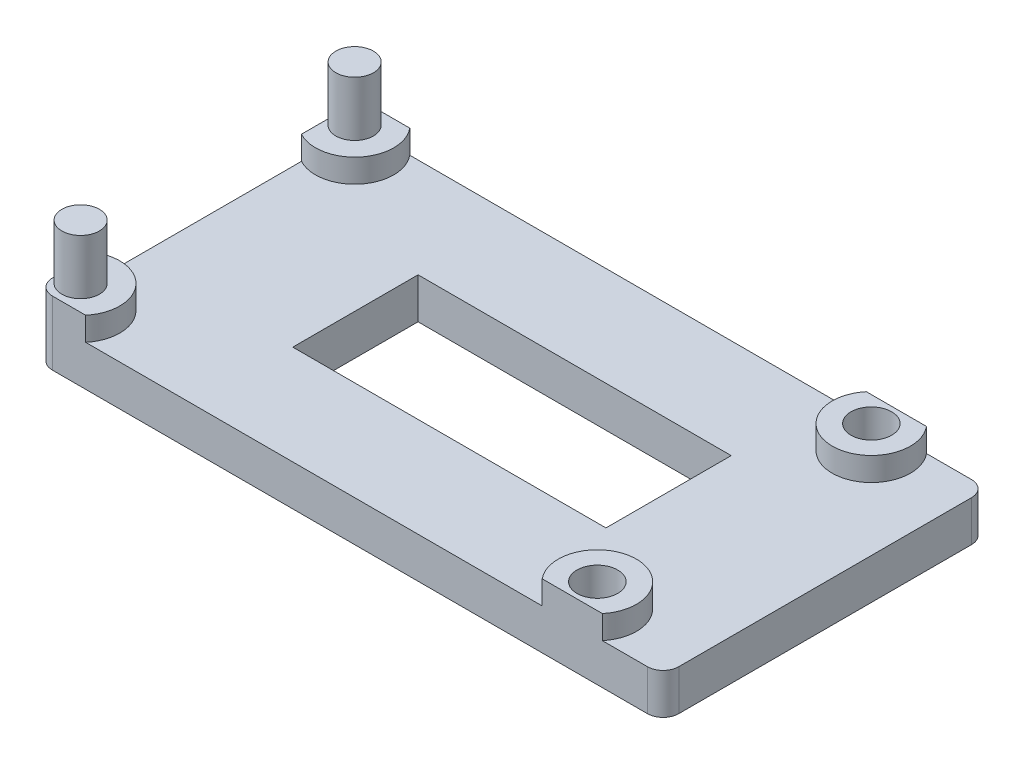
SolidWorks part; units mm, degrees
ref_plane "Front Plane" through (0, 0, 0) normal (0, 0, 1) x (1, 0, 0)
ref_plane "Top Plane" through (0, 0, 0) normal (0, 1, 0) x (1, 0, 0)
ref_plane "Right Plane" through (0, 0, 0) normal (1, 0, 0) x (0, 0, -1)
sketch "Sketch1" plane through (0, 0, 0) normal (0, 1, 0) x (1, 0, 0)
  line L1 (-20, -10.35) -> (20, -10.35)
  line L2 (-20, -10.35) -> (-20, 10.35)
  line L3 (-20, 10.35) -> (20, 10.35)
  line L4 (20, -10.35) -> (20, 10.35)
  line L5 (-20, -10.35) -> (20, 10.35) construction
  line L6 (-20, 10.35) -> (20, -10.35) construction
  point P0 (0, 0)
  dimension "D1" = 20.7
  dimension "D2" = 40
extrude "Boss-Extrude1" add sketch "Sketch1" along normal blind 4.1
sketch "Sketch2" plane through (0, 4.1, 0) normal (0, 1, 0) x (1, 0, 0)
  line L0 (-20, 10.35) -> (-20, -10.35) construction
  line L1 (-18.8, 8.75) -> (-18.8, -8.75) construction
  line L2 (-18.8, 0) -> (-20, 0) construction
  circle A0 centre (-18.8, 8.75) radius 1.2
  circle A1 centre (-18.8, -8.75) radius 1.2
  dimension "D1" = 2.4
  dimension "D2" = 17.5
extrude "Boss-Extrude2" add sketch "Sketch2" along normal blind 3.5
sketch "Sketch3" plane through (0, 4.1, 0) normal (0, 1, 0) x (1, 0, 0)
  line L0 (-18.8, 8.75) -> (20, 8.75) construction
  line L1 (20, -10.35) -> (20, 10.35) construction
  line L2 (-18.8, -8.75) -> (20, -8.75) construction
  line L3 (14.2, 8.75) -> (14.2, -8.75) construction
  circle A0 centre (14.2, 8.75) radius 1.3
  circle A1 centre (14.2, -8.75) radius 1.3
  dimension "D2" = 2.6
  dimension "D1" = 33
extrude "Cut-Extrude1" cut sketch "Sketch3" against normal through all
fillet "Fillet1" radius 1 4 edges at (-20, 2.05, -10.35) (20, 2.05, -10.35) (20, 2.05, 10.35) (-20, 2.05, 10.35)
sketch "Sketch4" plane through (0, 4.1, 0) normal (0, 1, 0) x (1, 0, 0)
  line L1 (-24.095, 13.8953) -> (24.8046, 13.8953)
  line L2 (-24.095, 13.8953) -> (-24.095, -14.4275)
  line L3 (-24.095, -14.4275) -> (24.8046, -14.4275)
  line L4 (24.8046, 13.8953) -> (24.8046, -14.4275)
  circle A0 centre (-18.8, 8.75) radius 2.5
  circle A1 centre (-18.8, -8.75) radius 2.5
  circle A2 centre (14.2, -8.75) radius 2.5
  circle A3 centre (14.2, 8.75) radius 2.5
  dimension "D1" = 5
extrude "Cut-Extrude2" cut sketch "Sketch4" against normal blind 1.5
sketch "Sketch5" plane through (0, 2.6, 0) normal (0, 1, 0) x (1, 0, 0)
  line L1 (-10, -4) -> (10, -4)
  line L2 (-10, -4) -> (-10, 4)
  line L3 (-10, 4) -> (10, 4)
  line L4 (10, -4) -> (10, 4)
  line L5 (-10, -4) -> (10, 4) construction
  line L6 (-10, 4) -> (10, -4) construction
  point P0 (0, 0)
  dimension "D1" = 8
  dimension "D2" = 20
extrude "Cut-Extrude3" cut sketch "Sketch5" against normal through all
